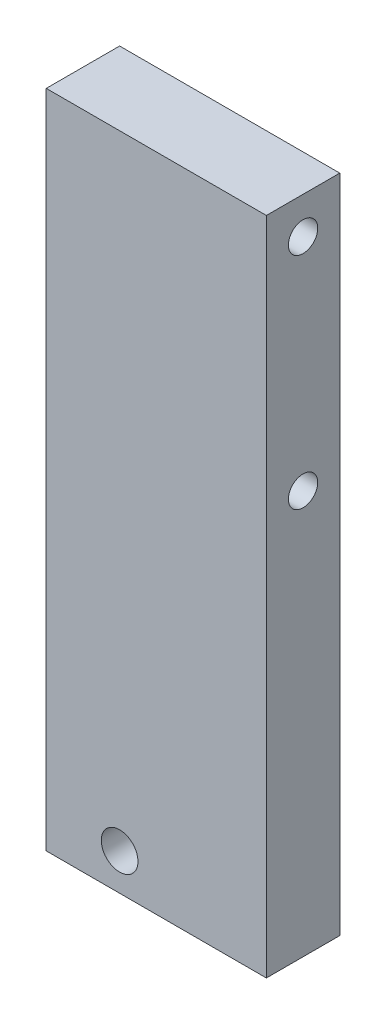
SolidWorks part; units mm, degrees
ref_plane "Front Plane" through (0, 0, 0) normal (0, 0, 1) x (1, 0, 0)
ref_plane "Top Plane" through (0, 0, 0) normal (0, 1, 0) x (1, 0, 0)
ref_plane "Right Plane" through (0, 0, 0) normal (1, 0, 0) x (0, 0, -1)
sketch "Sketch1" plane through (0, 0, 0) normal (0, 0, 1) x (1, 0, 0)
  line L0 (0, 90) -> (30, 90)
  line L1 (0, 0) -> (30, 0)
  line L2 (0, 0) -> (0, 90)
  line L4 (30, 0) -> (30, 90)
  dimension "D1" = 30
  dimension "D2" = 90
extrude "Boss-Extrude1" add sketch "Sketch1" along normal blind 10
sketch "Sketch3" plane through (30, 0, 0) normal (1, 0, 0) x (0, 0, -1)
  line L2 (-10, 0) -> (-10, 90) construction
  line L3 (-10, 90) -> (0, 90) construction
  circle A0 centre (-5, 85) radius 2
  circle A1 centre (-5, 55) radius 2
  dimension "D1" = 4
  dimension "D2" = 5
  dimension "D3" = 5
  dimension "D4" = 30
sketch "Sketch4" plane through (0, 0, 10) normal (0, 0, 1) x (1, 0, 0)
  line L1 (0, 90) -> (0, 0) construction
  line L2 (0, 0) -> (30, 0) construction
  circle A0 centre (10, 5) radius 2.5
  dimension "D1" = 5
  dimension "D2" = 10
  dimension "D3" = 5
extrude "Cut-Extrude2" cut sketch "Sketch4" against normal up to next
extrude "Cut-Extrude3" cut sketch "Sketch3" against normal through all
